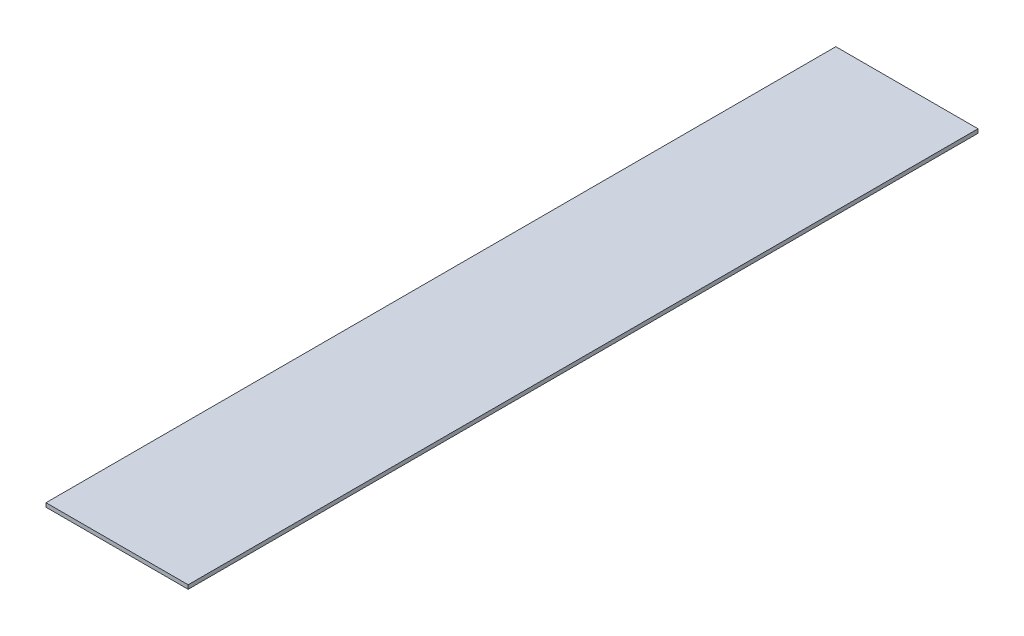
SolidWorks part; units mm, degrees
ref_plane "Front Plane" through (0, 0, 0) normal (0, 0, 1) x (1, 0, 0)
ref_plane "Top Plane" through (0, 0, 0) normal (0, 1, 0) x (1, 0, 0)
ref_plane "Right Plane" through (0, 0, 0) normal (1, 0, 0) x (0, 0, -1)
sketch "Sketch1" plane through (0, 0, 0) normal (0, 1, 0) x (1, 0, 0)
  line L1 (-54, 300) -> (54, 300)
  line L2 (-54, 300) -> (-54, -300)
  line L3 (-54, -300) -> (54, -300)
  line L4 (54, 300) -> (54, -300)
  line L5 (-54, 300) -> (54, -300) construction
  line L6 (-54, -300) -> (54, 300) construction
  point P0 (0, 0)
  dimension "D1" = 108
  dimension "D2" = 600
extrude "Boss-Extrude1" add sketch "Sketch1" along normal blind 3
